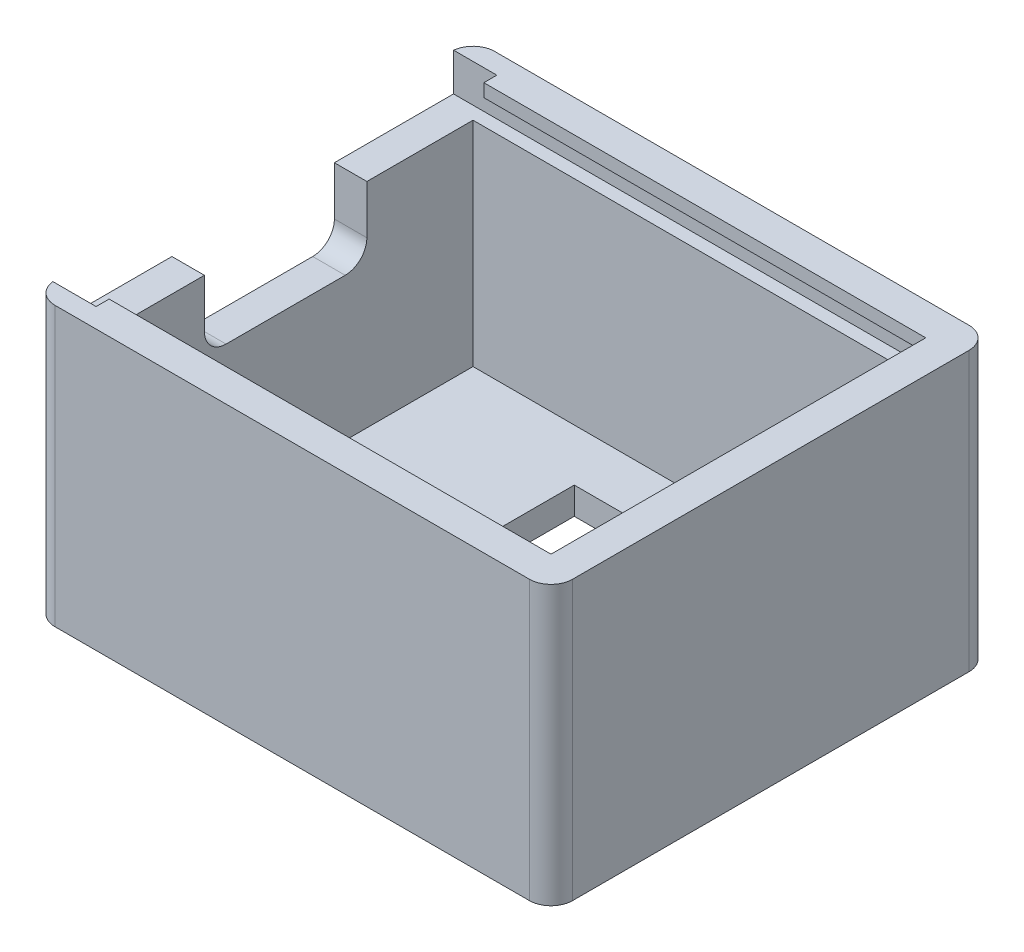
SolidWorks part; units mm, degrees
ref_plane "Front Plane" through (0, 0, 0) normal (0, 0, 1) x (1, 0, 0)
ref_plane "Top Plane" through (0, 0, 0) normal (0, 1, 0) x (1, 0, 0)
ref_plane "Right Plane" through (0, 0, 0) normal (1, 0, 0) x (0, 0, -1)
sketch "Sketch1" plane through (0, 0, 0) normal (0, 1, 0) x (1, 0, 0)
  line L1 (-23.9, 20.3) -> (23.9, 20.3)
  line L2 (-23.9, 20.3) -> (-23.9, -20.3)
  line L3 (-23.9, -20.3) -> (23.9, -20.3)
  line L4 (23.9, 20.3) -> (23.9, -20.3)
  line L5 (-23.9, 20.3) -> (23.9, -20.3) construction
  line L6 (-23.9, -20.3) -> (23.9, 20.3) construction
  point P0 (0, 0)
  dimension "D1" = 47.8
  dimension "D2" = 40.6
extrude "Boss-Extrude1" add sketch "Sketch1" along normal blind 25.7
sketch "Sketch2" plane through (0, 25.7, 0) normal (0, 1, 0) x (1, 0, 0)
  line L1 (-20.9, 17.3) -> (20.9, 17.3)
  line L2 (-20.9, 17.3) -> (-20.9, -17.3)
  line L3 (-20.9, -17.3) -> (20.9, -17.3)
  line L4 (20.9, 17.3) -> (20.9, -17.3)
  line L5 (-20.9, 17.3) -> (20.9, -17.3) construction
  line L6 (-20.9, -17.3) -> (20.9, 17.3) construction
  point P1 (0, 0)
  dimension "D1" = 41.8
  dimension "D2" = 34.6
extrude "Cut-Extrude1" cut sketch "Sketch2" against normal blind 23.2
fillet "Fillet1" radius 2 4 edges at (23.9, 12.85, -20.3) (-23.9, 12.85, -20.3) (-23.9, 12.85, 20.3) (23.9, 12.85, 20.3)
sketch "Sketch3" plane through (0, 2.5, 0) normal (0, 1, 0) x (1, 0, 0)
  line L1 (-6.75, 12.5) -> (18.25, 12.5)
  line L2 (-6.75, 12.5) -> (-6.75, -12.5)
  line L3 (-6.75, -12.5) -> (18.25, -12.5)
  line L4 (18.25, 12.5) -> (18.25, -12.5)
  line L5 (-6.75, 12.5) -> (18.25, -12.5) construction
  line L6 (-6.75, -12.5) -> (18.25, 12.5) construction
  point P0 (5.75, 0)
  dimension "D1" = 25
  dimension "D2" = 25
  dimension "D3" = 5.75
extrude "Cut-Extrude2" cut sketch "Sketch3" against normal through all
sketch "Sketch4" plane through (0, 0, 0) normal (0, 1, 0) x (1, 0, 0)
  line L0 (-23.9, 0) -> (23.9, 0) construction
  line L1 (-23.9, 18.3) -> (-23.9, -18.3) construction
  line L2 (23.9, -18.3) -> (23.9, 18.3) construction
  line L4 (-24.9, 18.5) -> (22.1, 18.5)
  line L5 (-24.9, 18.5) -> (-24.9, -18.5)
  line L6 (-24.9, -18.5) -> (22.1, -18.5)
  line L7 (22.1, 18.5) -> (22.1, -18.5)
  dimension "D1" = 37
  dimension "D2" = 22.1
  dimension "D3" = 24.9
extrude "Cut-Extrude3" cut sketch "Sketch4" along normal blind 2.3 from offset 22.2
sketch "Sketch6" plane through (-23.9, 0, 0) normal (-1, 0, 0) x (0, 0, 1)
  line L0 (-18.3, 25.7) -> (18.3, 25.7) construction
  line L1 (-18.5, 27.45) -> (18.5, 27.45)
  line L2 (-18.5, 27.45) -> (-18.5, 23.95)
  line L3 (-18.5, 23.95) -> (18.5, 23.95)
  line L4 (18.5, 27.45) -> (18.5, 23.95)
  line L5 (-18.5, 27.45) -> (18.5, 23.95) construction
  line L6 (-18.5, 23.95) -> (18.5, 27.45) construction
  point P0 (0, 25.7)
  dimension "D1" = 37
  dimension "D2" = 3.5
extrude "Cut-Extrude4" cut sketch "Sketch6" against normal blind 4
sketch "Sketch7" plane through (-23.9, 0, 0) normal (-1, 0, 0) x (0, 0, 1)
  line L0 (-18.3, 22.2) -> (18.3, 22.2) construction
  line L1 (-7.5, 28.7) -> (7.5, 28.7)
  line L2 (-7.5, 28.7) -> (-7.5, 15.7)
  line L3 (-7.5, 15.7) -> (7.5, 15.7)
  line L4 (7.5, 28.7) -> (7.5, 15.7)
  line L5 (-7.5, 28.7) -> (7.5, 15.7) construction
  line L6 (-7.5, 15.7) -> (7.5, 28.7) construction
  point P0 (0, 22.2)
  dimension "D1" = 15
  dimension "D2" = 13
extrude "Cut-Extrude5" cut sketch "Sketch7" against normal blind 4
fillet "Fillet2" radius 2 2 edges at (-22.4, 15.7, 7.5) (-22.4, 15.7, -7.5)
equation "\"board_w\"= 33.8"
equation "\"board_l\"= 41"
equation "\"stack_h\"= 19.5"
equation "\"module_w\"= 9.9"
equation "\"lens_d\"= 7.8"
equation "\"lens_from_end\"= 8"
equation "\"usb_w\"= 13"
equation "\"plug_h\"= 7"
equation "\"usb_from_back\"= 6"
equation "\"clear\"= 0.4"
equation "\"wall\"= 3"
equation "\"floor_t\"= 2.5"
equation "\"pocket_clear\"= 0.3"
equation "\"lens_clear\"= 0.6"
equation "\"plate_w\"= 16"
equation "\"plate_clear\"= 0.3"
equation "\"plate_t\"= 1.2"
equation "\"plate_seat\"= 0.8"
equation "\"window_d\"= 12"
equation "\"lid_t\"= 2"
equation "\"lid_gap\"= 1"
equation "\"groove_d\"= 1.2"
equation "\"groove_clear\"= 0.15"
equation "\"lip_top\"= 1.2"
equation "\"side_clear\"= 0.2"
equation "\"slide_clear\"= 0.2"
equation "\"ball_d\"= 16"
equation "\"ball_clear\"= 0.3"
equation "\"lip\"= 1.2"
equation "\"cup_floor\"= 1.2"
equation "\"cup_d\"= 26"
equation "\"slit_w\"= 1.5"
equation "\"slit_depth\"= 9"
equation "\"lug_w\"= 16"
equation "\"m3_hole\"= 3.4"
equation "\"m3_nut\"= 5.7"
equation "\"m3_nut_d\"= 2.6"
equation "\"boss_d\"= 20"
equation "\"boss_h\"= 8"
equation "\"nut_af\"= 11.4"
equation "\"nut_t\"= 5.8"
equation "\"screw_hole\"= 6.6"
equation "\"in_l\"= \"board_l\" + 2 * \"clear\""
equation "\"in_w\"= \"board_w\" + 2 * \"clear\""
equation "\"out_l\"= \"in_l\" + 2 * \"wall\""
equation "\"out_w\"= \"in_w\" + 2 * \"wall\""
equation "\"y_groove\"= \"floor_t\" - \"plate_seat\" + \"stack_h\" + \"lid_gap\""
equation "\"groove_h\"= \"lid_t\" + 2 * \"groove_clear\""
equation "\"tray_h\"= \"y_groove\" + \"groove_h\" + \"lip_top\""
equation "\"lid_w\"= \"in_w\" + 2 * \"groove_d\" - 2 * \"side_clear\""
equation "\"lid_right\"= \"in_l\" / 2 + \"groove_d\" - \"slide_clear\""
equation "\"lid_left\"= \"out_l\" / 2"
equation "\"open_d\"= \"ball_d\" - 2 * \"lip\""
equation "\"c_ball\"= sqr( ( ( \"ball_d\" + \"ball_clear\" ) / 2 ) ^ 2 - ( \"open_d\" / 2 ) ^ 2 )"
equation "\"cup_h\"= \"cup_floor\" + ( \"ball_d\" + \"ball_clear\" ) / 2 + \"c_ball\""
equation "\"lug_in\"= \"cup_d\" / 2 - 5"
equation "\"lug_out\"= \"cup_d\" / 2 + 4"
equation "\"D2@Sketch1\"=\"out_w\""
equation "\"D1@Sketch1\"=47.80mm"
equation "\"D1@Boss-Extrude1\"=\"tray_h\""
equation "\"D1@Sketch2\"=\"in_l\""
equation "\"D2@Sketch2\"=\"in_w\""
equation "\"D1@Cut-Extrude1\"=\"tray_h\"-\"floor_t\""
equation "\"D1@Sketch4\"=\"in_w\" + 2 * \"groove_d\""
equation "\"D2@Sketch4\"= \"in_l\" / 2 + \"groove_d\""
equation "\"D3@Sketch4\"=\"out_l\" / 2 + 1"
equation "\"D19@Cut-Extrude3\"=\"y_groove\""
equation "\"D1@Cut-Extrude3\"=\"groove_h\""
equation "\"D1@Sketch6\"=\"in_w\"+2 * \"groove_d\""
equation "\"D2@Sketch6\"=\"groove_h\"+ \"lip_top\""
equation "\"D1@Cut-Extrude4\"=\"wall\"+1"
equation "\"D1@Sketch7\"= \"lid_gap\" + \"groove_h\" + \"lip_top\" + \"usb_from_back\" + \"plug_h\" / 2 + 1"
equation "\"D2@Sketch7\"=\"usb_w\""
equation "\"D1@Cut-Extrude5\"=\"wall\"+1"
